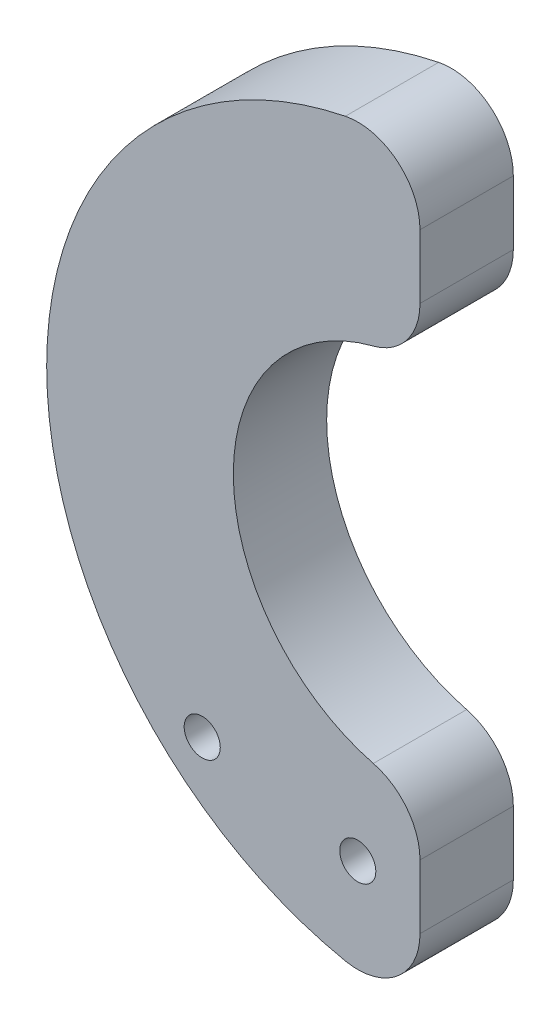
SolidWorks part; units mm, degrees
ref_plane "Front Plane" through (0, 0, 0) normal (0, 0, 1) x (1, 0, 0)
ref_plane "Top Plane" through (0, 0, 0) normal (0, 1, 0) x (1, 0, 0)
ref_plane "Right Plane" through (0, 0, 0) normal (1, 0, 0) x (0, 0, -1)
sketch "Finger Drawing" plane through (0, 0, 0) normal (0, 0, 1) x (1, 0, 0)
  line L2 (0, 15.5543) -> (0, 12.2967)
  line L3 (0, -12.2967) -> (0, -15.5543)
  arc A4 (-3.81, -18.6651) -> (-3.81, 18.6651) centre (0, 0) cw
  arc A5 (-2.3812, 9.2225) -> (-2.3812, -9.2225) centre (0, 0) ccw
  arc A6 (0, -15.5543) -> (-3.81, -18.6651) centre (-3.175, -15.5543) cw
  arc A7 (0, -12.2967) -> (-2.3812, -9.2225) centre (-3.175, -12.2967) ccw
  arc A8 (0, 15.5543) -> (-3.81, 18.6651) centre (-3.175, 15.5543) ccw
  arc A9 (0, 12.2967) -> (-2.3812, 9.2225) centre (-3.175, 12.2967) cw
  circle A10 centre (-3.175, -14.1944) radius 0.9208
  point P19 (0, 9.525)
  dimension "D1" = 9.525
  dimension "D2" = 19.05
  dimension "D3" = 3.175
  dimension "D4" = 1.8415
  dimension "D5" = 3.175
extrude "Finger Body" add sketch "Finger Drawing" along normal blind 4.7625 contours A5 A7 L3 A6 A4 A8 L2 A9
sketch "Sketch5" plane through (0, 0, 4.7625) normal (0, 0, 1) x (1, 0, 0)
  line L0 (0, -12.2967) -> (0, -15.5543) construction
  circle A0 centre (-3.175, -13.9303) radius 0.9208
  circle A2 centre (0, 0) radius 14.2875 construction
  circle A3 centre (0, 0) radius 16.6687 construction
  circle A4 centre (-11.1125, -12.4242) radius 0.9208
  dimension "D1" = 1.8415
  dimension "D3" = 28.575
  dimension "D4" = 33.3375
  dimension "D6" = 1.8415
  dimension "D2" = 3.175
  dimension "D5" = 11.1125
extrude "Finger Pin Holes" cut sketch "Sketch5" against normal through all contours A0 | A4
